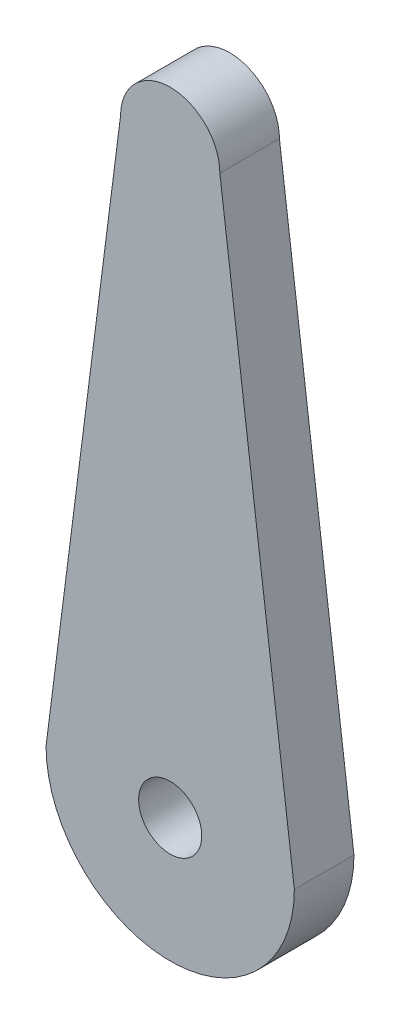
SolidWorks part; units mm, degrees
ref_plane "Front Plane" through (0, 0, 0) normal (1, 0, 0) x (0, 1, 0)
ref_plane "Top Plane" through (0, 0, 0) normal (0, 0, 1) x (0, 1, 0)
ref_plane "Right Plane" through (0, 0, 0) normal (0, 1, 0) x (-1, 0, 0)
sketch "Sketch1" plane through (0, 0, 0) normal (0, 0, 1) x (0, 1, 0)
  line L1 (0, 12.5) -> (58.7, 5)
  line L2 (0, -12.5) -> (58.7, -5)
  arc A0 (0, 12.5) -> (0, -12.5) centre (0, 0) ccw
  arc A1 (58.7, -5) -> (58.7, 5) centre (58.7, 0) ccw
  dimension "D1" = 25
  dimension "D3" = 10
extrude "Boss-Extrude1" add sketch "Sketch1" along normal blind 6
sketch "Sketch2" plane through (0, 0, 6) normal (0, 0, 1) x (1, 0, 0)
  circle A0 centre (0, 0) radius 3.175
  dimension "D1" = 6.35
extrude "Cut-Extrude1" cut sketch "Sketch2" against normal blind 21
